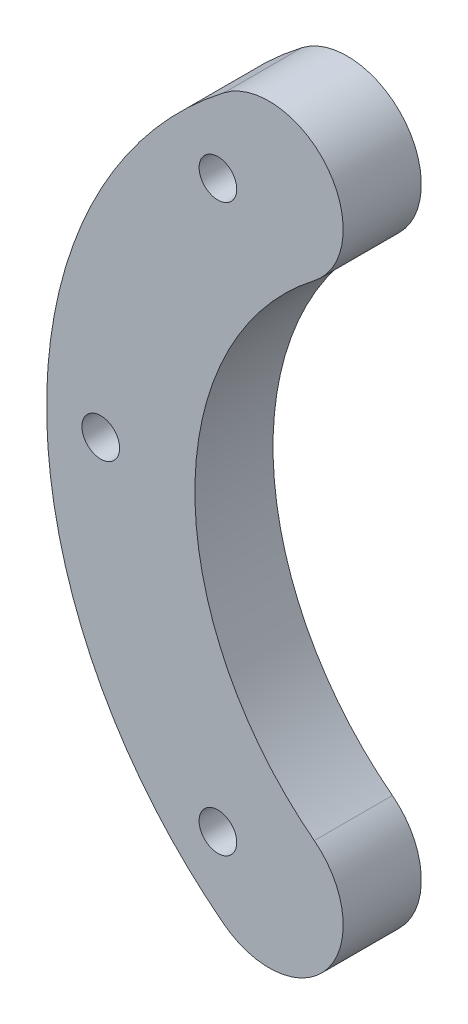
SolidWorks part; units mm, degrees
ref_plane "前视基准面" through (0, 0, 0) normal (0, 0, 1) x (1, 0, 0)
ref_plane "上视基准面" through (0, 0, 0) normal (0, 1, 0) x (1, 0, 0)
ref_plane "右视基准面" through (0, 0, 0) normal (1, 0, 0) x (0, 0, -1)
other "Configuration Table"
sketch "草图1" plane through (0, 0, 0) normal (0, 0, 1) x (1, 0, 0)
  circle A0 centre (0, 0) radius 48.25
  circle A2 centre (0, 0) radius 32.5
  circle A3 centre (0, 0) radius 42.5 construction
  circle A4 centre (0, 42.5) radius 2
  circle A5 centre (30.052, 30.052) radius 2
  circle A6 centre (42.5, 0) radius 2
  circle A7 centre (30.052, -30.052) radius 2
  circle A8 centre (0, -42.5) radius 2
  circle A9 centre (-30.052, -30.052) radius 2
  circle A10 centre (-42.5, 0) radius 2
  circle A11 centre (-30.052, 30.052) radius 2
  point P23 (0, 0)
  dimension "D1" = 96.5
  dimension "D2" = 65
  dimension "D3" = 85
  dimension "D4" = 4
  dimension "D6" = 45
  dimension "D5" = 8
extrude "凸台-拉伸1" add sketch "草图1" along normal blind 8.3
sketch "草图2" plane through (0, 0, 8.3) normal (0, 0, 1) x (1, 0, 0)
  line L0 (-48.25, 0) -> (48.25, 0) construction
  circle A0 centre (0, 0) radius 32.5 construction
  circle A1 centre (0, 0) radius 48.25
  circle A2 centre (0, 0) radius 48.25
  circle A3 centre (0, 0) radius 32.5
  circle A4 centre (-24.6199, 32) radius 7.875
  circle A5 centre (-24.6199, -32) radius 7.875
  circle M7 centre (0, -42.5) radius 2
  circle M8 centre (42.5, 0) radius 2
  circle M9 centre (0, 42.5) radius 2
  circle M10 centre (0, 0) radius 48.25
  circle M11 centre (0, 0) radius 32.5
  circle M12 centre (30.052, 30.052) radius 2
  circle M13 centre (30.052, -30.052) radius 2
  dimension "D2" = 64
  dimension "D1" = 0
extrude "切除-拉伸1" cut sketch "草图2" against normal blind 46 contours L0 A4 M11 M8 M10 M12 M9 | L0 A3 A5 A2 M8 M7 M13
